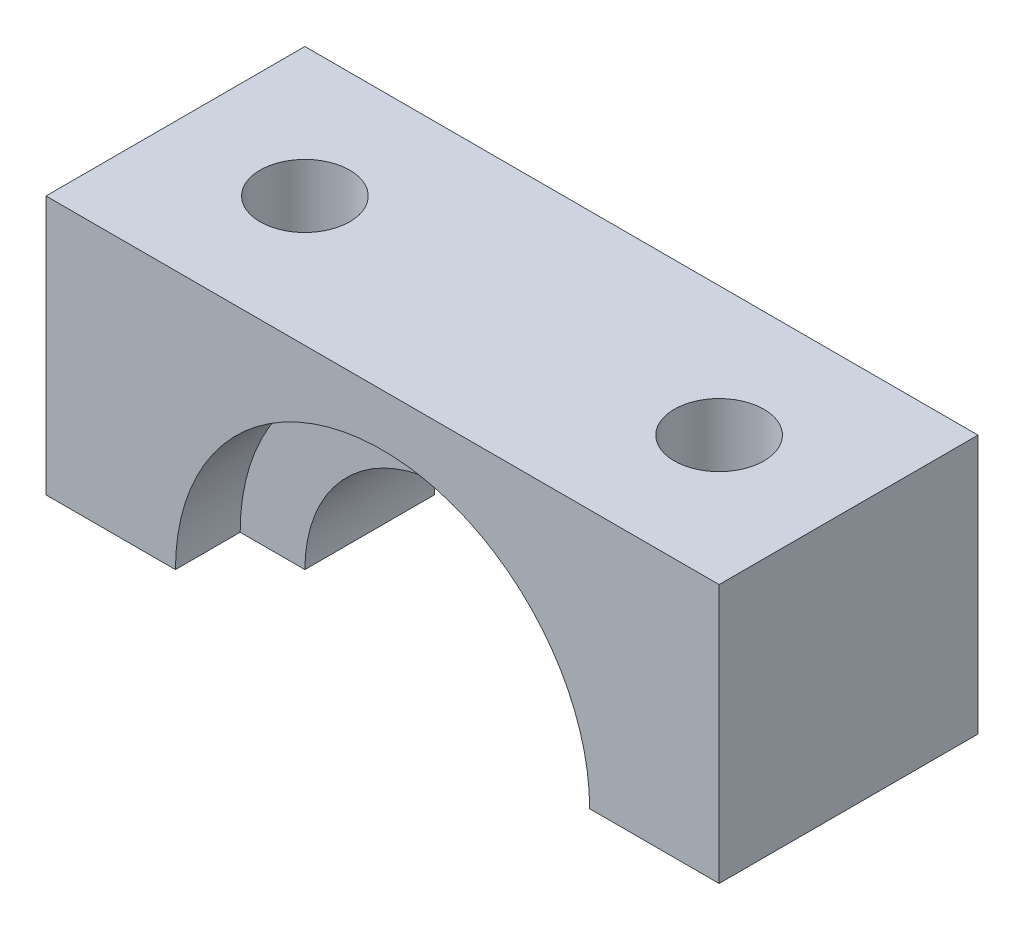
SolidWorks part; units mm, degrees
ref_plane "Plano frontal" through (0, 0, 0) normal (0, 0, 1) x (1, 0, 0)
ref_plane "Plano superior" through (0, 0, 0) normal (0, 1, 0) x (1, 0, 0)
ref_plane "Plano direito" through (0, 0, 0) normal (1, 0, 0) x (0, 0, -1)
sketch "Esboço1" plane through (0, 0, 0) normal (0, 0, 1) x (1, 0, 0)
  line L0 (-5.5, 0) -> (-13, 0)
  line L1 (-13, 0) -> (-13, 10)
  line L2 (-13, 10) -> (13, 10)
  line L3 (13, 10) -> (13, 0)
  line L4 (13, 0) -> (5.5, 0)
  arc A0 (5.5, 0) -> (-5.5, 0) centre (0, 0) ccw
  dimension "D1" = 5.5
  dimension "D2" = 26
  dimension "D3" = 10
extrude "Ressalto-extrusão1" add sketch "Esboço1" along normal mid plane 5
sketch "Esboço3" plane through (0, 0, 0) normal (0, 0, 1) x (1, 0, 0)
  line L0 (-13, 10) -> (-13, 0)
  line L1 (-13, 0) -> (-8, 0)
  line L2 (8, 0) -> (13, 0)
  line L3 (13, 0) -> (13, 10)
  line L4 (13, 10) -> (-13, 10)
  arc A0 (8, 0) -> (-8, 0) centre (0, 0) ccw
  dimension "D1" = 8
extrude "Ressalto-extrusão2" add sketch "Esboço3" along normal mid plane 10
sketch "Esboço2" plane through (0, 0, 0) normal (0, -1, 0) x (1, 0, 0)
  line L0 (0, 0) -> (0, 9.5392) construction
  line L1 (-5.5, 2.5) -> (-5.5, -2.5) construction
  circle A0 centre (-8, 0) radius 1.7309
  circle A1 centre (8, 0) radius 1.7309
  point P7 (-5.5, 0)
  dimension "D1" = 16
extrude "Corte-extrusão1" cut sketch "Esboço2" against normal blind 15
